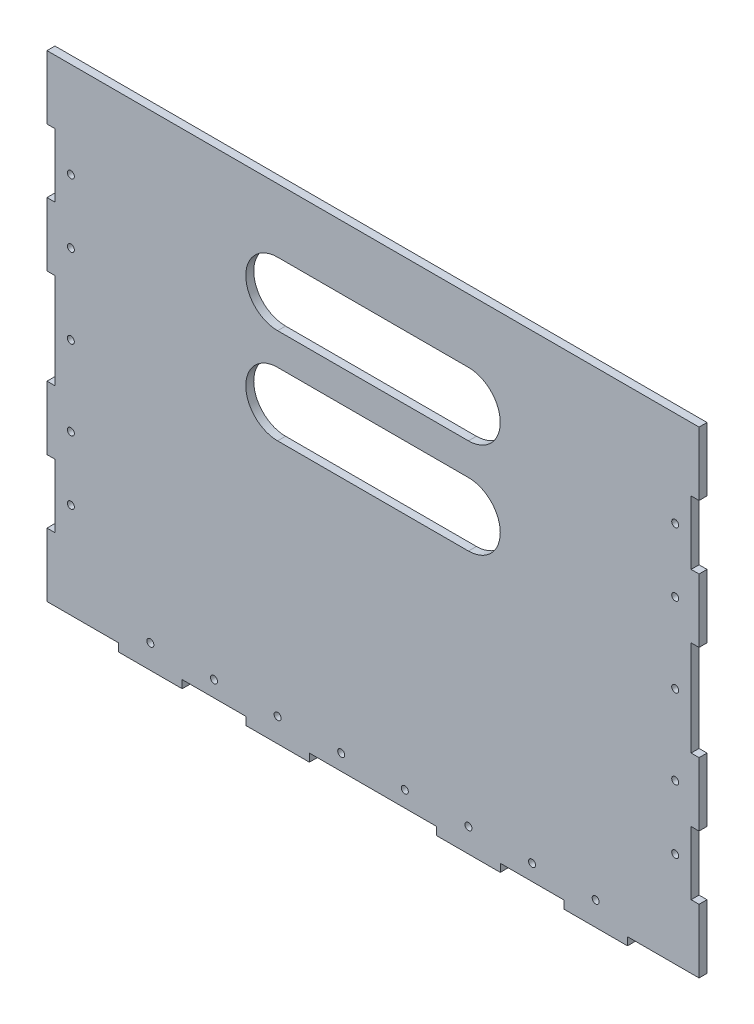
SolidWorks part; units mm, degrees
ref_plane "前视基准面" through (0, 0, 0) normal (0, 0, 1) x (1, 0, 0)
ref_plane "上视基准面" through (0, 0, 0) normal (0, 1, 0) x (1, 0, 0)
ref_plane "右视基准面" through (0, 0, 0) normal (1, 0, 0) x (0, 0, -1)
sketch "草图1" plane through (0, 0, 0) normal (0, 0, 1) x (1, 0, 0)
  line L2 (-200, 150) -> (200, 150)
  line L3 (200, -150) -> (200, -110)
  line L4 (-200, -150) -> (-200, -110)
  line L5 (-200, -150) -> (-160, -150)
  line L6 (-200, -150) -> (-160, -150)
  line L7 (-160, -150) -> (-160, -155)
  line L8 (-160, -155) -> (-120, -155)
  line L9 (-120, -155) -> (-120, -150)
  line L10 (-120, -150) -> (-80, -150)
  line L11 (-80, -150) -> (-80, -155)
  line L12 (-80, -155) -> (-40, -155)
  line L13 (-40, -155) -> (-40, -150)
  line L14 (-40, -150) -> (40, -150)
  line L15 (40, -150) -> (40, -155)
  line L16 (40, -155) -> (80, -155)
  line L17 (80, -155) -> (80, -150)
  line L18 (80, -150) -> (120, -150)
  line L19 (120, -150) -> (120, -155)
  line L20 (120, -155) -> (160, -155)
  line L21 (160, -155) -> (160, -150)
  line L22 (80, -150) -> (120, -150)
  line L23 (-120, -150) -> (-80, -150)
  line L24 (-40, -150) -> (40, -150)
  line L25 (160, -150) -> (200, -150)
  line L26 (-200, 110) -> (-200, 150)
  line L27 (-200, -70) -> (-200, -30)
  line L28 (-205, -30) -> (-205, 30)
  line L29 (-205, 30) -> (-200, 30)
  line L30 (-200, 30) -> (-200, 70)
  line L31 (-200, 70) -> (-205, 70)
  line L32 (-205, 70) -> (-205, 110)
  line L33 (-205, 110) -> (-200, 110)
  line L34 (-205, -30) -> (-200, -30)
  line L35 (-200, -70) -> (-205, -70)
  line L36 (-205, -70) -> (-205, -110)
  line L37 (-205, -110) -> (-200, -110)
  line L38 (-200, 30) -> (-200, 70)
  line L39 (200, 110) -> (200, 150)
  line L40 (205, -70) -> (205, -110)
  line L41 (205, -110) -> (200, -110)
  line L42 (200, -70) -> (205, -70)
  line L43 (205, -30) -> (200, -30)
  line L44 (205, -30) -> (205, 30)
  line L45 (205, 30) -> (200, 30)
  line L46 (200, 70) -> (205, 70)
  line L47 (205, 70) -> (205, 110)
  line L48 (205, 110) -> (200, 110)
  line L49 (200, 30) -> (200, 70)
  line L50 (200, -70) -> (200, -30)
  circle A0 centre (-140, -140) radius 2.2
  circle A1 centre (-100, -140) radius 2.2
  circle A2 centre (-60, -140) radius 2.2
  circle A3 centre (-20, -140) radius 2.2
  circle A4 centre (20, -140) radius 2.2
  circle A5 centre (60, -140) radius 2.2
  circle A6 centre (100, -140) radius 2.2
  circle A7 centre (140, -140) radius 2.2
  circle A8 centre (-190, 110) radius 2.2
  circle A9 centre (-190, 70) radius 2.2
  circle A10 centre (-190, 30) radius 2.2
  circle A11 centre (-190, -30) radius 2.2
  circle A12 centre (-190, -70) radius 2.2
  circle A13 centre (-190, -110) radius 2.2
  circle A14 centre (190, -110) radius 2.2
  circle A15 centre (190, -70) radius 2.2
  circle A16 centre (190, -30) radius 2.2
  circle A17 centre (190, 30) radius 2.2
  circle A18 centre (190, 70) radius 2.2
  circle A19 centre (190, 110) radius 2.2
extrude "凸台-拉伸1" add sketch "草图1" along normal blind 5 contours L42 L50 L43 L44 L45 L49 L46 L47 L48 L39 L2 L26 L33 L32 L31 L30 L29 L28 L34 L27 L35 L36 L37 L4 L5 L7 L8 L9 L10 L11 L12 L13 L14 L15 L16 L17 L18 L19 L20 L21 L25 L3 L41 L40 A18 A16 A14
sketch "草图2" plane through (0, 0, 5) normal (0, 0, 1) x (1, 0, 0)
  line L0 (-205, 110) -> (-200, 110)
  line L1 (-205, 110) -> (-205, -110.2824)
  line L2 (-200, 110) -> (-200, -110.2824)
  line L3 (-205, -110.2824) -> (-200, -110.2824)
  line L4 (200, 110) -> (205, 110)
  line L5 (200, 110) -> (200, -109.8687)
  line L6 (205, 110) -> (205, -109.8687)
  line L7 (200, -109.8687) -> (205, -109.8687)
extrude "切除-拉伸1" cut sketch "草图2" against normal blind 10
sketch "草图3" plane through (0, 0, 5) normal (0, 0, 1) x (1, 0, 0)
  line L0 (-200, 150) -> (-205, 150)
  line L1 (-205, 150) -> (-205, 110)
  line L2 (-205, 110) -> (-200, 110)
  line L3 (-200, -150) -> (-200, 150) construction
  line L4 (-200, 30) -> (-200, 70)
  line L5 (-200, 70) -> (-205, 70)
  line L6 (-205, 70) -> (-205, 30)
  line L7 (-205, 30) -> (-200, 30)
  line L9 (-200, -30) -> (-205, -30)
  line L10 (-205, -30) -> (-205, -70)
  line L11 (-205, -70) -> (-200, -70)
  line L13 (-200, -110) -> (-205, -110)
  line L14 (-205, -110) -> (-205, -150)
  line L15 (-205, -150) -> (-200, -150)
  line L16 (-200, -70) -> (-200, -30)
  line L19 (205, -150) -> (200, -150)
  line L20 (205, -110) -> (205, -150)
  line L21 (200, -110) -> (205, -110)
  line L23 (205, -70) -> (200, -70)
  line L24 (205, -30) -> (205, -70)
  line L25 (200, -30) -> (205, -30)
  line L27 (205, 30) -> (200, 30)
  line L28 (205, 70) -> (205, 30)
  line L29 (200, 70) -> (205, 70)
  line L31 (205, 110) -> (200, 110)
  line L32 (205, 150) -> (205, 110)
  line L33 (200, 150) -> (205, 150)
  line L34 (-200, -150) -> (-200, -110)
  line L35 (200, 150) -> (200, 110)
  line L36 (-200, 110) -> (-200, 150)
  line L37 (200, 70) -> (200, 30)
  line L38 (200, -30) -> (200, -70)
  line L39 (200, -110) -> (200, -150)
extrude "凸台-拉伸3" add sketch "草图3" against normal blind 5
sketch "草图4" plane through (0, 0, 5) normal (0, 0, 1) x (1, 0, 0)
  line L0 (-193.4037, 139.8055) -> (197.0175, 139.8055)
  line L1 (-193.4037, 139.8055) -> (-193.4037, -124.8847)
  line L2 (197.0175, 139.8055) -> (197.0175, -124.8847)
  line L3 (-193.4037, -124.8847) -> (197.0175, -124.8847)
extrude "凸台-拉伸4" add sketch "草图4" against normal blind 5
sketch "草图5" plane through (0, 0, 5) normal (0, 0, 1) x (1, 0, 0)
  circle A11 centre (-190, 90) radius 2.2
  circle A12 centre (-190, 50) radius 2.2
  circle A13 centre (-190, 0) radius 2.2
  circle A14 centre (-190, -50) radius 2.2
  circle A15 centre (-190, -90) radius 2.2
  circle A16 centre (190, -90) radius 2.2
  circle A17 centre (190, -50) radius 2.2
  circle A18 centre (190, 0) radius 2.2
  circle A19 centre (190, 50) radius 2.2
  circle A20 centre (190, 90) radius 2.2
extrude "切除-拉伸2" cut sketch "草图5" against normal blind 5
sketch "草图6" plane through (0, 0, 5) normal (0, 0, 1) x (1, 0, 0)
  line L0 (-60, 30) -> (60, 30) construction
  line L1 (-60, 50) -> (60, 50)
  line L2 (-60, 10) -> (60, 10)
  line L5 (-60, 90) -> (60, 90) construction
  line L6 (-60, 110) -> (60, 110)
  line L7 (-60, 70) -> (60, 70)
  arc A0 (-60, 110) -> (-60, 70) centre (-60, 90) ccw
  arc A1 (60, 70) -> (60, 110) centre (60, 90) ccw
  arc A2 (-60, 50) -> (-60, 10) centre (-60, 30) ccw
  arc A3 (60, 10) -> (60, 50) centre (60, 30) ccw
  point P4 (0, 90)
  point P5 (0, 30)
  point P9 (0, 90)
  dimension "D1" = 2
extrude "切除-拉伸3" cut sketch "草图6" against normal blind 10
